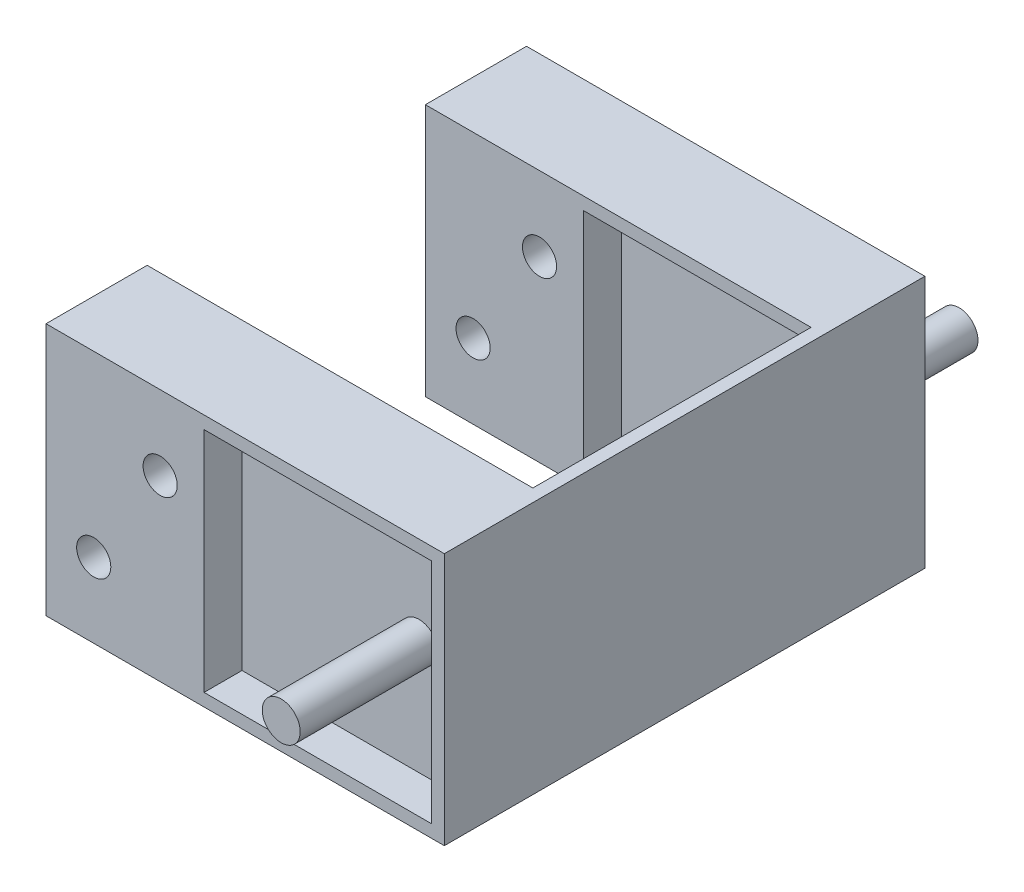
SolidWorks part; units mm, degrees
ref_plane "Front Plane" through (0, 0, 0) normal (0, 0, 1) x (1, 0, 0)
ref_plane "Top Plane" through (0, 0, 0) normal (0, 1, 0) x (1, 0, 0)
ref_plane "Right Plane" through (0, 0, 0) normal (1, 0, 0) x (0, 0, -1)
sketch "Sketch1" plane through (0, 0, 0) normal (0, 0, 1) x (1, 0, 0)
  line L0 (-14.5303, 0) -> (16.9697, 0)
  line L1 (16.9697, 0) -> (16.9697, 20)
  line L2 (16.9697, 20) -> (-14.5303, 20)
  line L3 (-14.5303, 20) -> (-14.5303, 0)
  dimension "D1" = 31.5
  dimension "D2" = 20
extrude "Extrude-Thin1" add sketch "Sketch1" along normal blind 8 thin thin type one direction reverse wall 1
sketch "Sketch2" plane through (0, 0, 0) normal (0, 0, 1) x (1, 0, 0)
  line L1 (-14.5303, 20) -> (16.9697, 20)
  line L2 (-14.5303, 20) -> (-14.5303, 0)
  line L3 (-14.5303, 0) -> (16.9697, 0)
  line L4 (16.9697, 20) -> (16.9697, 0)
extrude "Boss-Extrude1" add sketch "Sketch2" along normal mid plane 2 from offset 4
sketch "Sketch3" plane through (0, 0, 5) normal (0, 0, 1) x (1, 0, 0)
  line L1 (16.9697, 10) -> (-14.5303, 10) construction
  line L2 (-14.5303, 20) -> (-14.5303, 0) construction
  circle A0 centre (11.9697, 10) radius 1.5
  point P2 (-2.0303, 10)
  point P3 (-0.0303, 10)
  dimension "D1" = 5
  dimension "D2" = 3
  dimension "D3" = 12.5
  dimension "D4" = 12
  dimension "D5" = 2
sketch "Sketch4" plane through (0, 0, 8) normal (0, 0, 1) x (1, 0, 0)
  line L0 (-14.5303, 0) -> (16.9697, 0) construction
  line L1 (-14.5303, 20) -> (-2.0303, 20)
  line L2 (-14.5303, 20) -> (-14.5303, 0)
  line L3 (-14.5303, 0) -> (-2.0303, 0)
  line L4 (-2.0303, 20) -> (-2.0303, 0)
  dimension "D1" = 12.5
extrude "Boss-Extrude2" add sketch "Sketch4" along direction (0, 0, -1) on the side against the normal blind 8
sketch "Sketch5" plane through (0, 0, 8) normal (0, 0, 1) x (1, 0, 0)
  line L0 (-14.5303, 0) -> (-1.7291, 20) construction
  line L1 (16.9697, 20) -> (-14.5303, 20) construction
  circle A0 centre (-10.7567, 5.8957) radius 1.35
  circle A1 centre (-5.5027, 14.1043) radius 1.35
  point P8 (0, 0)
  point P9 (-1.7286, 22.4534)
  point P10 (-2.0303, 20)
  point P13 (-3.9118, 13.349)
  dimension "D3" = 2.7
  dimension "D4" = 2.7
  dimension "D1" = 7
  dimension "D2" = 7
extrude "Cut-Extrude2" cut sketch "Sketch5" against normal blind 8
sketch "Sketch8" plane through (0, 0, 0) normal (0, 0, -1) x (-1, 0, 0)
  line L1 (2.0303, 19) -> (-15.9697, 19)
  line L2 (2.0303, 19) -> (2.0303, 1)
  line L3 (2.0303, 1) -> (-15.9697, 1)
  line L4 (-15.9697, 19) -> (-15.9697, 1)
sketch "Sketch11" plane through (0, 0, 0) normal (0, 0, -1) x (-1, 0, 0)
  line L1 (2.0303, 19) -> (-15.9697, 19)
  line L2 (2.0303, 19) -> (2.0303, 1)
  line L3 (2.0303, 1) -> (-15.9697, 1)
  line L4 (-15.9697, 19) -> (-15.9697, 1)
sketch "Sketch12" plane through (0, 0, 0) normal (0, 0, -1) x (-1, 0, 0)
  line L0 (-15.9697, 0) -> (-15.9697, 20)
  line L1 (14.5303, 0) -> (-16.9697, 0) construction
  line L2 (-16.9697, 20) -> (14.5303, 20) construction
  line L3 (-15.9697, 20) -> (-16.9697, 20)
  line L4 (-16.9697, 20) -> (-16.9697, 0)
  line L5 (-16.9697, 0) -> (-15.9697, 0)
sketch "Sketch13" plane through (0, 0, 0) normal (0, 0, -1) x (-1, 0, 0)
  line L0 (14.5303, 20) -> (-1.2582, 20) construction
  line L1 (-16.9697, 20) -> (14.5303, 20) construction
  line L2 (-1.2582, 20) -> (-1.2582, 0) construction
  line L3 (14.5303, 0) -> (-16.9697, 0) construction
sketch "Sketch14" plane through (0, 0, 8) normal (0, 0, 1) x (1, 0, 0)
  line L1 (16.9697, 20) -> (-14.5303, 20)
  line L2 (16.9697, 20) -> (16.9697, 0)
  line L3 (16.9697, 0) -> (-14.5303, 0)
  line L4 (-14.5303, 20) -> (-14.5303, 0)
sketch "Sketch15" plane through (0, 0, 8) normal (0, 0, 1) x (1, 0, 0)
  circle A0 centre (-5.5027, 14.1043) radius 1.35
  circle A1 centre (-10.7567, 5.8957) radius 1.35
ref_plane "Plane1" through (0, 0, -11) normal (0, 0, 1) x (1, 0, 0)
sketch "Sketch16" plane through (0, 0, 8) normal (0, 0, 1) x (1, 0, 0)
  line L1 (16.9697, 0) -> (7.3402, 0)
  line L2 (16.9697, 0) -> (16.9697, -3.0636)
  line L3 (16.9697, -3.0636) -> (7.3402, -3.0636)
  line L4 (7.3402, 0) -> (7.3402, -3.0636)
extrude "Boss-Extrude4" add sketch "Sketch12" along normal blind 22
mirror "Mirror5" about plane through (0, 0, -11) normal (0, 0, 1) of bodies 114
sketch "Sketch17" plane through (16.9697, 0, 0) normal (1, 0, 0) x (0, 0, -1)
  line L0 (-8, 0) -> (-15.9, -0.9073) construction
  dimension "D1" = 7.9
extrude "Boss-Extrude6" add sketch "Sketch3" against normal blind 53.6 from vertex at 10.9 contours A0 starting at point (16.9697, -0.9073, 15.9)
